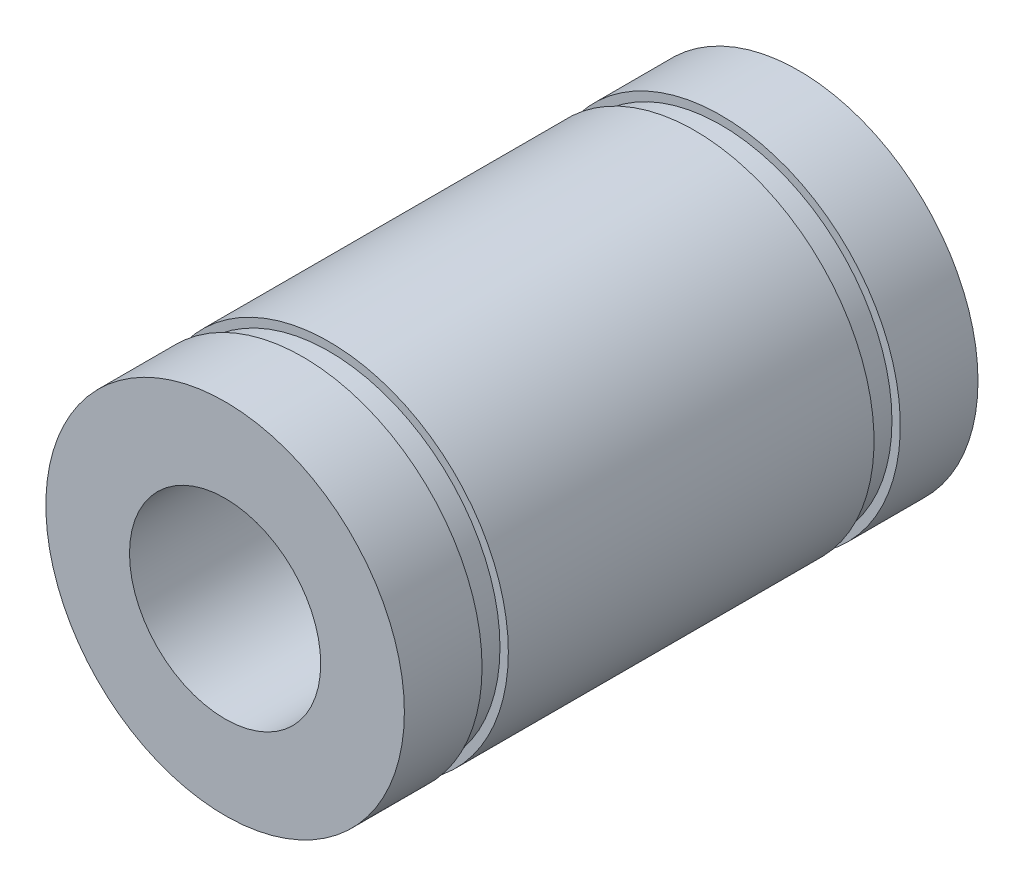
SolidWorks part; units mm, degrees
ref_plane "Front" through (0, 0, 0) normal (0, 0, 1) x (1, 0, 0)
ref_plane "Top" through (0, 0, 0) normal (0, 1, 0) x (1, 0, 0)
ref_plane "Right" through (0, 0, 0) normal (1, 0, 0) x (0, 0, -1)
sketch "Sketch1" plane through (0, 0, 0) normal (0, 0, 1) x (1, 0, 0)
  circle A0 centre (0, 0) radius 7.5
  dimension "D1" = 15
extrude "Boss-Extrude1" add sketch "Sketch1" along normal mid plane 24
sketch "Sketch2" plane through (0, 0, 12) normal (0, 0, 1) x (1, 0, 0)
  circle A0 centre (0, 0) radius 4
  dimension "D1" = 8
extrude "Cut-Extrude1" cut sketch "Sketch2" against normal through all
sketch "Sketch3" plane through (0, 0, 12) normal (0, 0, 1) x (1, 0, 0)
  circle A0 centre (0, 0) radius 7.15
  dimension "D1" = 14.3
extrude "Cut-Extrude2" cut sketch "Sketch3" against normal blind 1.1 from offset 3.25 flip side to cut offset against normal yes
mirror "Mirror1" about plane through (0, 0, 0) normal (0, 0, 1) of "Cut-Extrude2"
